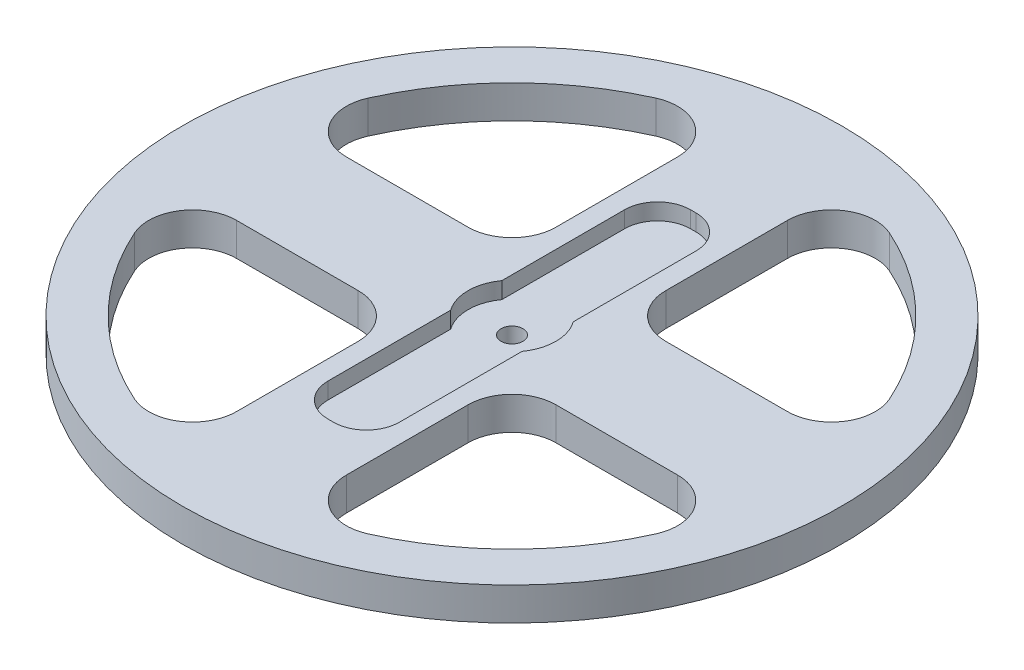
SolidWorks part; units mm, degrees
ref_plane "Front Plane" through (0, 0, 0) normal (0, 0, 1) x (1, 0, 0)
ref_plane "Top Plane" through (0, 0, 0) normal (0, 1, 0) x (1, 0, 0)
ref_plane "Right Plane" through (0, 0, 0) normal (1, 0, 0) x (0, 0, -1)
sketch "Sketch1" plane through (0, 0, 0) normal (0, 1, 0) x (1, 0, 0)
  circle A0 centre (0, 0) radius 30
  dimension "D1" = 60
extrude "Boss-Extrude1" add sketch "Sketch1" along normal blind 3
sketch "Sketch2" plane through (0, 3, 0) normal (0, 1, 0) x (1, 0, 0)
  line L0 (-3.25, 16.5) -> (-3.25, 2.3318)
  line L1 (-3.25, -16.5) -> (3.25, -16.5)
  line L2 (3.25, -16.5) -> (3.25, -2.3318)
  line L3 (3.25, 16.5) -> (-3.25, 16.5)
  line L4 (-3.25, -2.3318) -> (-3.25, -16.5)
  line L5 (3.25, 2.3318) -> (3.25, 16.5)
  arc A0 (-3.25, 2.3318) -> (-3.25, -2.3318) centre (0, 0) ccw
  arc A1 (3.25, -2.3318) -> (3.25, 2.3318) centre (0, 0) ccw
  point P6 (0, 0)
  point P8 (0, 0)
  dimension "D1" = 8
  dimension "D2" = 33
  dimension "D3" = 16.5
  dimension "D4" = 6.5
  dimension "D5" = 3.25
extrude "Cut-Extrude1" cut sketch "Sketch2" against normal blind 1.5
sketch "Sketch3" plane through (0, 3, 0) normal (0, 1, 0) x (1, 0, 0)
  line L0 (-5, -25.5147) -> (-5, -5)
  line L1 (5, -25.5147) -> (5, -5)
  line L2 (-25.5147, -5) -> (-5, -5)
  line L3 (25.5147, 5) -> (5, 5)
  line L4 (5, -5) -> (25.5147, -5)
  line L5 (-5, 5) -> (-5, 25.5147)
  line L6 (-5, 5) -> (-25.5147, 5)
  line L7 (5, 5) -> (5, 25.5147)
  arc A0 (5, -25.5147) -> (25.5147, -5) centre (0, 0) ccw
  arc A1 (-25.5147, -5) -> (-5, -25.5147) centre (0, 0) ccw
  arc A2 (25.5147, 5) -> (5, 25.5147) centre (0, 0) ccw
  arc A3 (-5, 25.5147) -> (-25.5147, 5) centre (0, 0) ccw
  dimension "D1" = 52
  dimension "D2" = 10
  dimension "D3" = 5
  dimension "D4" = 10
  dimension "D5" = 5
extrude "Cut-Extrude2" cut sketch "Sketch3" against normal blind 3
sketch "Sketch4" plane through (0, 0, 0) normal (0, -1, 0) x (1, 0, 0)
  circle A0 centre (0, 0) radius 1
  dimension "D1" = 2
extrude "Cut-Extrude3" cut sketch "Sketch4" against normal blind 3
fillet "Fillet1" radius 4 12 edges at (25.5147, 1.5, -5) (5, 1.5, -25.5147) (5, 1.5, 5) (25.5147, 1.5, 5) (5, 1.5, 25.5147) (5, 1.5, -5) (-25.5147, 1.5, -5) (-5, 1.5, -5) (-5, 1.5, -25.5147) (-25.5147, 1.5, 5) (-5, 1.5, 5) (-5, 1.5, 25.5147)
fillet "Fillet2" radius 3 4 edges at (-3.25, 2.25, -16.5) (-3.25, 2.25, 16.5) (3.25, 2.25, 16.5) (3.25, 2.25, -16.5)
equation "\"main od\"= 60"
equation "\"connector length\"= 33"
equation "\"connetor width\"= 6.5"
equation "\"connector id\"= 8"
equation "\"thick\"= 3"
equation "\"D1@Sketch1\"=\"main od\""
equation "\"D1@Boss-Extrude1\"=\"thick\""
equation "\"D1@Sketch2\"=\"connector id\""
equation "\"D2@Sketch2\"=\"connector length\""
equation "\"D3@Sketch2\"=\"connector length\"/2"
equation "\"D4@Sketch2\"=\"connetor width\""
equation "\"D5@Sketch2\"=\"connetor width\"/2"
equation "\"main id\"= 52"
equation "\"D1@Sketch3\"=\"main id\""
equation "\"spoke width\"= 10"
equation "\"D2@Sketch3\"=\"spoke width\""
equation "\"D3@Sketch3\"=\"spoke width\"/2"
equation "\"D4@Sketch3\"=\"spoke width\""
equation "\"D5@Sketch3\"=\"spoke width\"/2"
equation "\"D1@Cut-Extrude2\"=\"thick\""
equation "\"fillet\"= 4"
equation "\"screw hole\"= 2"
equation "\"D1@Sketch4\"=\"screw hole\""
equation "\"D1@Cut-Extrude3\"=\"thick\""
equation "\"D1@Fillet1\"=\"fillet\""
